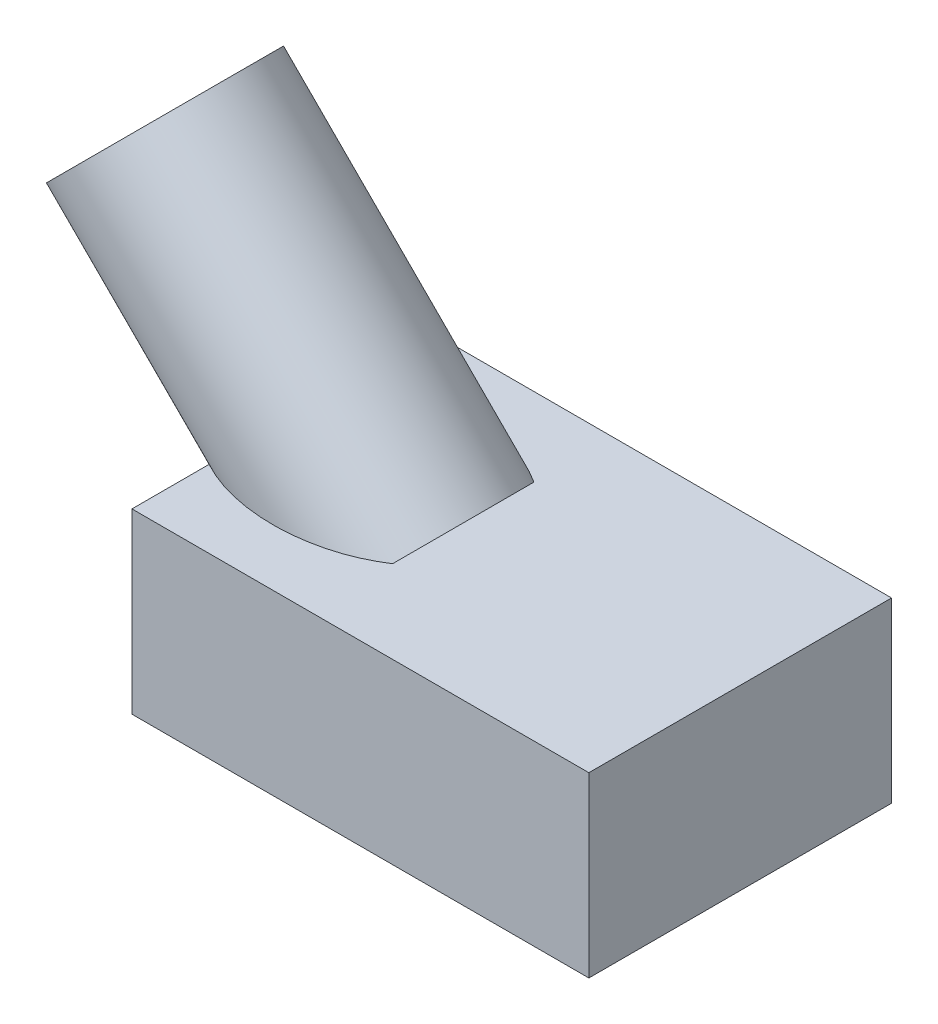
SolidWorks part; units mm, degrees
ref_plane "Front Plane" through (0, 0, 0) normal (0, 0, 1) x (1, 0, 0)
ref_plane "Top Plane" through (0, 0, 0) normal (0, 1, 0) x (1, 0, 0)
ref_plane "Right Plane" through (0, 0, 0) normal (1, 0, 0) x (0, 0, -1)
sketch "Sketch2" plane through (0, 0, 0) normal (0, 1, 0) x (1, 0, 0)
  line L1 (-73.661, 41.9458) -> (54.8365, 41.9458)
  line L2 (-73.661, 41.9458) -> (-73.661, -43.1735)
  line L3 (-73.661, -43.1735) -> (54.8365, -43.1735)
  line L4 (54.8365, 41.9458) -> (54.8365, -43.1735)
ref_plane "Plane1" through (-36.8305, 36.8305, 0) normal (-0.7071, 0.7071, 0) x (0, 0, 1)
extrude "Boss-Extrude1" add sketch "Sketch2" along normal blind 50
sketch "Sketch3" plane through (-36.8305, 36.8305, 0) normal (-0.7071, 0.7071, 0) x (0, 0, 1)
  circle A0 centre (0, 0) radius 27.2256
extrude "Boss-Extrude2" add sketch "Sketch3" along normal blind 100
ref_plane "Plane2" through (-9.6863, 24.8934, 0) normal (-0.3626, 0.9319, 0) x (0.9319, 0.3626, 0)
ref_plane "Plane3" through (-9.6863, 24.8934, 0) normal (-0.3626, 0.9319, 0) x (0.9319, 0.3626, 0)
ref_plane "Plane4" through (54.8365, 50, 0.6138) normal (0, 0, -1) x (-1, 0, 0)
